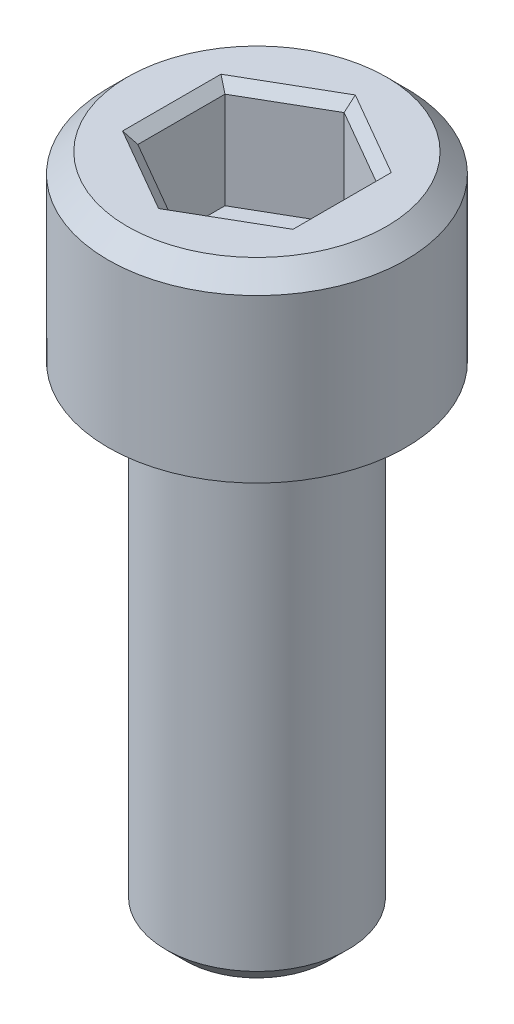
SolidWorks part; units mm, degrees
material "Plain Carbon Steel"
ref_plane "Front Plane" through (0, 0, 0) normal (0, 0, 1) x (1, 0, 0)
ref_plane "Top Plane" through (0, 0, 0) normal (0, 1, 0) x (1, 0, 0)
ref_plane "Right Plane" through (0, 0, 0) normal (1, 0, 0) x (0, 0, -1)
sketch "Sketch1" plane through (0, 0, 0) normal (0, 0, 1) x (1, 0, 0)
  line L0 (-3.9116, -4.7752) -> (0, -4.7752)
  line L1 (0, -4.7752) -> (0, 0)
  line L2 (0, 0) -> (-3.9116, 0)
  line L3 (-3.9116, 0) -> (-3.9116, -4.7752)
  line L4 (0, -4.7752) -> (0, 0) construction
  dimension "D1" = 3.9116
  dimension "D2" = 4.7752
revolve "Revolve1" add sketch "Sketch1" angle 360 about L4
sketch "Sketch2" plane through (0, -4.7752, 0) normal (0, -1, 0) x (1, 0, 0)
  circle A0 centre (0, 0) radius 2.3876
  circle A1 centre (0, 0) radius 3.9116 construction
  dimension "D1" = 4.7752
extrude "Boss-Extrude1" add sketch "Sketch2" along normal blind 12.7
sketch "Sketch3" plane through (0, 0, 0) normal (0, 1, 0) x (-1, 0, 0)
  line L7 (1.9844, -1.1457) -> (1.9844, 1.1457)
  line L8 (1.9844, 1.1457) -> (0, 2.2914)
  line L9 (0, 2.2914) -> (-1.9844, 1.1457)
  line L10 (-1.9844, 1.1457) -> (-1.9844, -1.1457)
  line L11 (-1.9844, -1.1457) -> (0, -2.2914)
  line L12 (0, -2.2914) -> (1.9844, -1.1457)
  circle A0 centre (0, 0) radius 1.9844 construction
  dimension "D1" = 4.5827
extrude "Cut-Extrude1" cut sketch "Sketch3" against normal blind 2.794
chamfer "Chamfer1" distance 0.508 angle 45 2 edges at (0, -17.4752, -2.3876) (0, 0, 3.9116)
chamfer "Chamfer2" distance 0.254 angle 45 6 edges at (-0.9922, 0, 1.7185) (0.9922, 0, 1.7185) (1.9844, 0, 0) (0.9922, 0, -1.7185) (-0.9922, 0, -1.7185) (-1.9844, 0, 0)
